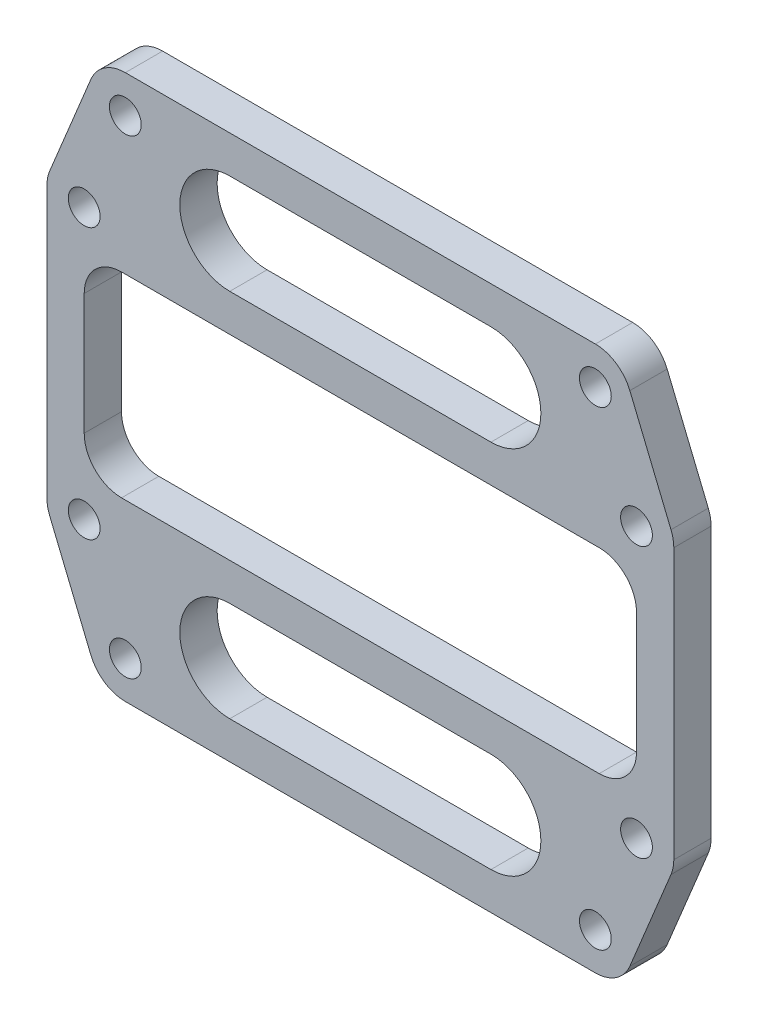
SolidWorks part; units mm, degrees
material "ABS PC"
ref_plane "Front Plane" through (0, 0, 0) normal (0, 0, 1) x (1, 0, 0)
ref_plane "Top Plane" through (0, 0, 0) normal (0, 1, 0) x (1, 0, 0)
ref_plane "Right Plane" through (0, 0, 0) normal (1, 0, 0) x (0, 0, -1)
sketch "Sketch1" plane through (0, 0, 0) normal (0, 0, 1) x (1, 0, 0)
  line L0 (-96.5856, 71.7653) -> (-49.5856, 48.7653) construction
  line L1 (-93.0856, 80.2653) -> (-53.0856, 40.2653) construction
  line L2 (-96.0214, 81.4742) -> (-99.5214, 72.9742)
  line L3 (-96.5856, 68.5903) -> (-49.5856, 68.5903)
  line L4 (-96.5856, 68.5903) -> (-96.5856, 51.9403)
  line L5 (-96.5856, 51.9403) -> (-49.5856, 51.9403)
  line L6 (-49.5856, 68.5903) -> (-49.5856, 51.9403)
  line L7 (-93.0856, 83.4403) -> (-53.0856, 83.4403)
  line L8 (-46.4106, 71.7653) -> (-46.4106, 48.7653)
  line L9 (-53.0856, 37.0903) -> (-93.0856, 37.0903)
  line L10 (-99.7606, 48.7653) -> (-99.7606, 71.7653)
  line L11 (-99.5214, 47.5564) -> (-96.0214, 39.0564)
  line L12 (-50.1497, 39.0564) -> (-46.6497, 47.5564)
  line L13 (-50.1497, 81.4742) -> (-46.6497, 72.9742)
  circle A0 centre (-53.0856, 40.2653) radius 3.175
  circle A1 centre (-53.0856, 40.2653) radius 1.55 construction
  circle A2 centre (-93.0856, 80.2653) radius 3.175
  circle A3 centre (-93.0856, 40.2653) radius 3.175
  circle A4 centre (-53.0856, 80.2653) radius 3.175
  circle A5 centre (-96.5856, 71.7653) radius 3.175
  circle A6 centre (-49.5856, 71.7653) radius 3.175
  circle A7 centre (-96.5856, 48.7653) radius 3.175
  circle A8 centre (-49.5856, 48.7653) radius 3.175
  point P21 (-73.0856, 60.2653)
  point P22 (-73.0856, 60.2653)
  point P39 (-48.578, 76.4405)
  point P40 (-48.6838, 71.8078)
  point P43 (-45.7354, 64.4295)
  point P46 (0, 0)
  point P47 (0, 0)
  dimension "D1" = 6.35
  dimension "D2" = 6.35
  dimension "D3" = 47
  dimension "D4" = 23
extrude "Boss-Extrude1" add sketch "Sketch1" along normal blind 3.175 contours A6 L13 A4 L7 A2 L2 A5 L3 | A2 | A5 | A6 | A4 | A8 L8 A6 L6 | A8 | A0 | A8 L5 A7 L11 A3 L9 A0 L12 | A3 | A7 | A7 L4 A5 L10
fillet "Fillet1" radius 3.175 4 edges at (-49.5856, 51.9403, 1.5875) (-49.5856, 68.5903, 1.5875) (-96.5856, 68.5903, 1.5875) (-96.5856, 51.9403, 1.5875)
hole_wizard "#2 Clearance Hole1" positions "Sketch2" profile "Sketch3" hole size "#2" standard "ANSI Inch" end condition through all
sketch "Sketch2" plane through (0, 0, 3.175) normal (0, 0, 1) x (1, 0, 0)
  point P0 (-93.0856, 80.2653)
  point P8 (-53.0856, 80.2653)
  point P17 (-53.0856, 40.2653)
  point P20 (-93.0856, 40.2653)
  point P24 (0, 0)
  point P25 (0, 0)
  point P26 (0, 0)
sketch "Sketch3" plane through (-93.0856, 80.2653, 3.175) normal (1, 0, 0) x (0, -1, 0)
  line L0 (0, 0) -> (0, 3.175)
  line L1 (0, 3.175) -> (1.3525, 3.175)
  line L2 (1.3525, 3.175) -> (1.3525, 0)
  line L5 (1.3525, 0) -> (0, 0)
  line L11 (0, -6.35) -> (0, 107.95) construction
  dimension "Thru Hole Dia." = 2.7051
  dimension "Thru Hole Depth" = 3.175
hole_wizard "#2 Clearance Hole2" positions "Sketch4" profile "Sketch5" hole size "#2" standard "ANSI Inch" end condition through all
sketch "Sketch4" plane through (0, 0, 3.175) normal (0, 0, 1) x (1, 0, 0)
  point P0 (-96.5856, 71.7653)
  point P3 (-49.5856, 71.7653)
  point P6 (-49.5856, 48.7653)
  point P9 (-96.5856, 48.7653)
sketch "Sketch5" plane through (-96.5856, 71.7653, 3.175) normal (1, 0, 0) x (0, -1, 0)
  line L0 (0, 0) -> (0, 3.175)
  line L1 (0, 3.175) -> (1.3525, 3.175)
  line L2 (1.3525, 3.175) -> (1.3525, 0)
  line L5 (1.3525, 0) -> (0, 0)
  line L11 (0, -6.35) -> (0, 107.95) construction
  dimension "Thru Hole Dia." = 2.7051
  dimension "Thru Hole Depth" = 3.175
sketch "Sketch6" plane through (0, 0, 3.175) normal (0, 0, 1) x (1, 0, 0)
  line L0 (-73.0856, 83.4403) -> (-73.0856, 68.5903) construction
  line L1 (-93.0856, 83.4403) -> (-53.0856, 83.4403) construction
  line L2 (-93.4106, 68.5903) -> (-52.7606, 68.5903) construction
  line L3 (-84.1981, 76.0153) -> (-61.9731, 76.0153) construction
  line L5 (-84.1981, 80.2653) -> (-61.9731, 80.2653)
  line L6 (-84.1981, 71.7653) -> (-61.9731, 71.7653)
  line L7 (-96.5856, 60.2653) -> (-49.5856, 60.2653) construction
  line L8 (-96.5856, 65.4153) -> (-96.5856, 55.1153) construction
  line L9 (-49.5856, 65.4153) -> (-49.5856, 55.1153) construction
  line L10 (-84.1981, 44.5153) -> (-61.9731, 44.5153) construction
  line L11 (-84.1981, 40.2653) -> (-61.9731, 40.2653)
  line L12 (-84.1981, 48.7653) -> (-61.9731, 48.7653)
  arc A0 (-84.1981, 80.2653) -> (-84.1981, 71.7653) centre (-84.1981, 76.0153) ccw
  arc A1 (-61.9731, 71.7653) -> (-61.9731, 80.2653) centre (-61.9731, 76.0153) ccw
  arc A2 (-84.1981, 40.2653) -> (-84.1981, 48.7653) centre (-84.1981, 44.5153) cw
  arc A3 (-61.9731, 48.7653) -> (-61.9731, 40.2653) centre (-61.9731, 44.5153) cw
  point P8 (-73.0856, 76.0153)
  point P21 (-73.0856, 44.5153)
  dimension "D1" = 3.175
  dimension "D2" = 22.225
extrude "Cut-Extrude1" cut sketch "Sketch6" against normal through all
